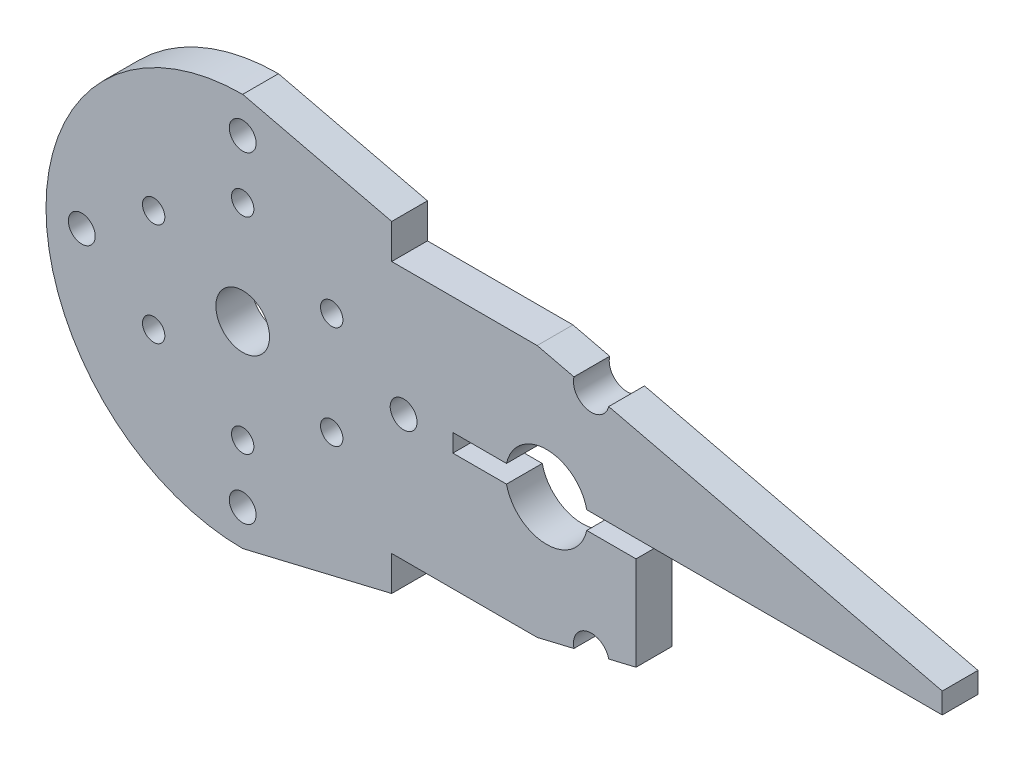
SolidWorks part; units mm, degrees
ref_plane "前视基准面" through (0, 0, 0) normal (0, 0, 1) x (1, 0, 0)
ref_plane "上视基准面" through (0, 0, 0) normal (0, 1, 0) x (1, 0, 0)
ref_plane "右视基准面" through (0, 0, 0) normal (1, 0, 0) x (0, 0, -1)
sketch "草图1" plane through (0, 0, 0) normal (0, 0, 1) x (1, 0, 0)
  line L0 (-38.999, 0) -> (5.001, 0) construction
  line L1 (-38.999, 22.002) -> (5.001, 22.002) construction
  line L6 (-38.999, 22.002) -> (-38.999, -22.002) construction
  line L7 (-38.999, -22.002) -> (5.001, -22.002) construction
  line L11 (5.001, 22.002) -> (5.001, -22.002) construction
  line L12 (5.001, 22.002) -> (5.001, 1) construction
  line L13 (-15.489, 1) -> (-9.489, 1)
  line L31 (-15.489, 1) -> (-15.489, -1)
  line L35 (-15.489, -1) -> (-9.489, -1)
  line L36 (-9.489, 1) -> (-9.489, -1) construction
  line L37 (5.001, 1) -> (-0.509, 1)
  line L39 (5.001, -1) -> (-0.509, -1)
  line L40 (-0.509, 1) -> (-0.509, -1) construction
  line L41 (5.001, -1) -> (5.001, -22.002) construction
  line L42 (5.001, 11.501) -> (-38.999, 22.002)
  line L43 (5.001, -11.501) -> (-38.999, -22.002)
  line L44 (5.001, 11.501) -> (5.001, 1) construction
  line L45 (5.001, -1) -> (5.001, -11.501)
  line L46 (5.001, 1) -> (39.2548, 1)
  line L47 (5.001, 11.501) -> (39.2548, 3.326)
  line L48 (39.2548, 3.326) -> (39.2548, 1)
  circle A3 centre (-38.999, 0) radius 3
  circle A6 centre (-38.999, 0) radius 11.5 construction
  circle A7 centre (-38.999, -11.5) radius 1.25
  circle A18 centre (-38.999, 0) radius 22.002 construction
  circle A30 centre (-48.9583, -5.75) radius 1.25
  circle A31 centre (-48.9583, 5.75) radius 1.25
  circle A32 centre (-38.999, 11.5) radius 1.25
  circle A33 centre (-29.0397, 5.75) radius 1.25
  circle A34 centre (-29.0397, -5.75) radius 1.25
  arc A35 (-38.999, 22.002) -> (-38.999, -22.002) centre (-38.999, 0) ccw
  circle A37 centre (-4.999, 0) radius 4.6 construction
  arc A38 (-0.509, 1) -> (-9.489, 1) centre (-4.999, 0) ccw
  arc A39 (-0.509, -1) -> (-9.489, -1) centre (-4.999, 0) cw
  circle A40 centre (-38.999, -18.002) radius 1.5
  circle A41 centre (-38.999, 18.002) radius 1.5
  circle A42 centre (-57.001, 0) radius 1.5
  circle A43 centre (-13.999, -5.75) radius 1.5 construction
  circle A44 centre (-13.999, 5.75) radius 1.5 construction
  circle A45 centre (-38.999, 0) radius 18.002 construction
  circle A46 centre (-20.997, 0) radius 1.5
  point P45 (-61.001, 0)
  dimension "D3" = 6
  dimension "D4" = 44
  dimension "D5" = 9.2
  dimension "D6" = 10
  dimension "D7" = 23
  dimension "D8" = 2.5
  dimension "D9" = 2
  dimension "D11" = 4
  dimension "D14" = 25
  dimension "D2" = 44.004
  dimension "D12" = 4
  dimension "D13" = 4
  dimension "D1" = 6
  dimension "D10" = 6
extrude "凸台-拉伸1" add sketch "草图1" along normal blind 4
sketch "草图2" plane through (0, 0, 0) normal (0, 0, -1) x (-1, 0, 0)
  line L0 (-39.2548, 3.326) -> (38.999, 22.002) construction
  line L1 (38.999, -22.002) -> (-5.001, -11.501) construction
  line L2 (15.489, 1) -> (9.489, 1) construction
  line L3 (4.1121, 14.14) -> (22.3299, 14.14)
  line L4 (4.1121, 14.14) -> (4.1121, 28.2304)
  line L5 (4.1121, 28.2304) -> (22.3299, 28.2304)
  line L6 (22.3299, 14.14) -> (22.3299, 28.2304)
  line L7 (20.997, 0) -> (4.7868, 0) construction
  line L8 (4.1121, -14.14) -> (4.1121, -28.2304)
  line L9 (4.1121, -28.2304) -> (22.3299, -28.2304)
  line L10 (22.3299, -14.14) -> (22.3299, -28.2304)
  line L11 (4.1121, -14.14) -> (22.3299, -14.14)
  circle A0 centre (0, 12.6945) radius 2
  circle A1 centre (0, -12.6945) radius 2
  dimension "D1" = 13.14
extrude "切除-拉伸1" cut sketch "草图2" against normal blind 4
